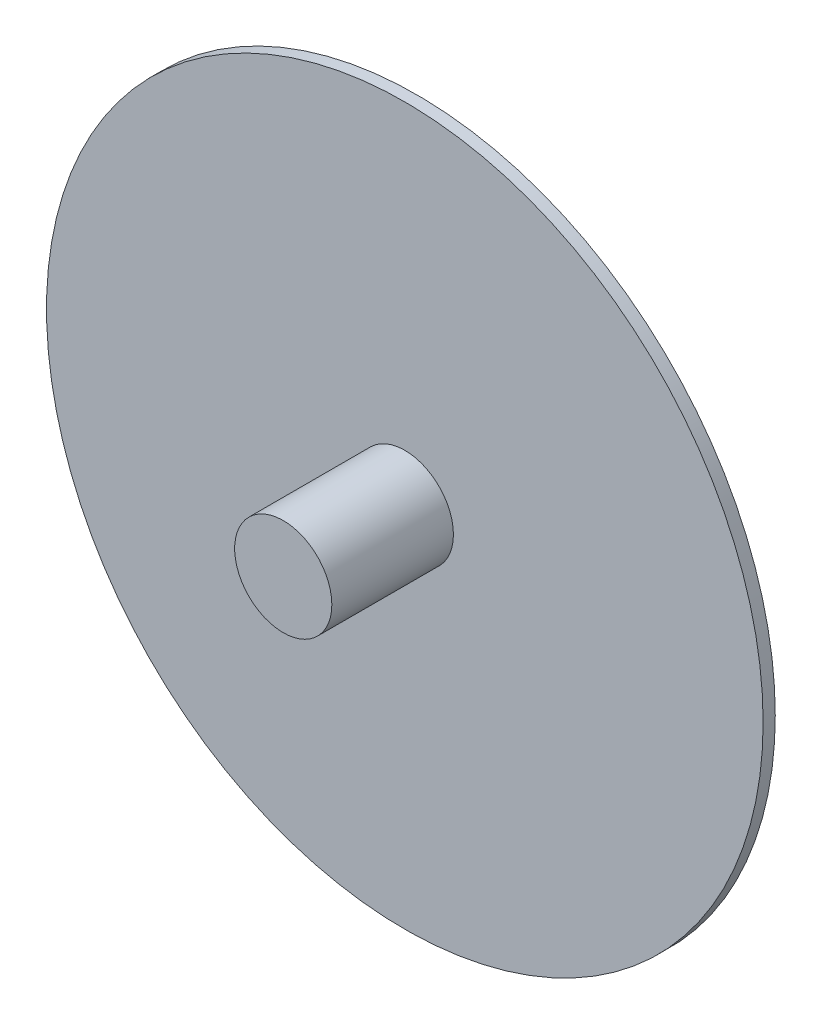
SolidWorks part; units mm, degrees
ref_plane "前视基准面" through (0, 0, 0) normal (0, 0, 1) x (1, 0, 0)
ref_plane "上视基准面" through (0, 0, 0) normal (0, 1, 0) x (1, 0, 0)
ref_plane "右视基准面" through (0, 0, 0) normal (1, 0, 0) x (0, 0, -1)
sketch "草图1" plane through (0, 0, 0) normal (0, 0, 1) x (1, 0, 0)
  circle A0 centre (0, -0.6544) radius 29.5
  dimension "D1" = 59
extrude "凸台-拉伸2" add sketch "草图1" along normal blind 1
sketch "草图2" plane through (0, 0, 1) normal (0, 0, 1) x (1, 0, 0)
  circle A0 centre (0, 0) radius 4
extrude "凸台-拉伸3" add sketch "草图2" along normal blind 10.01
